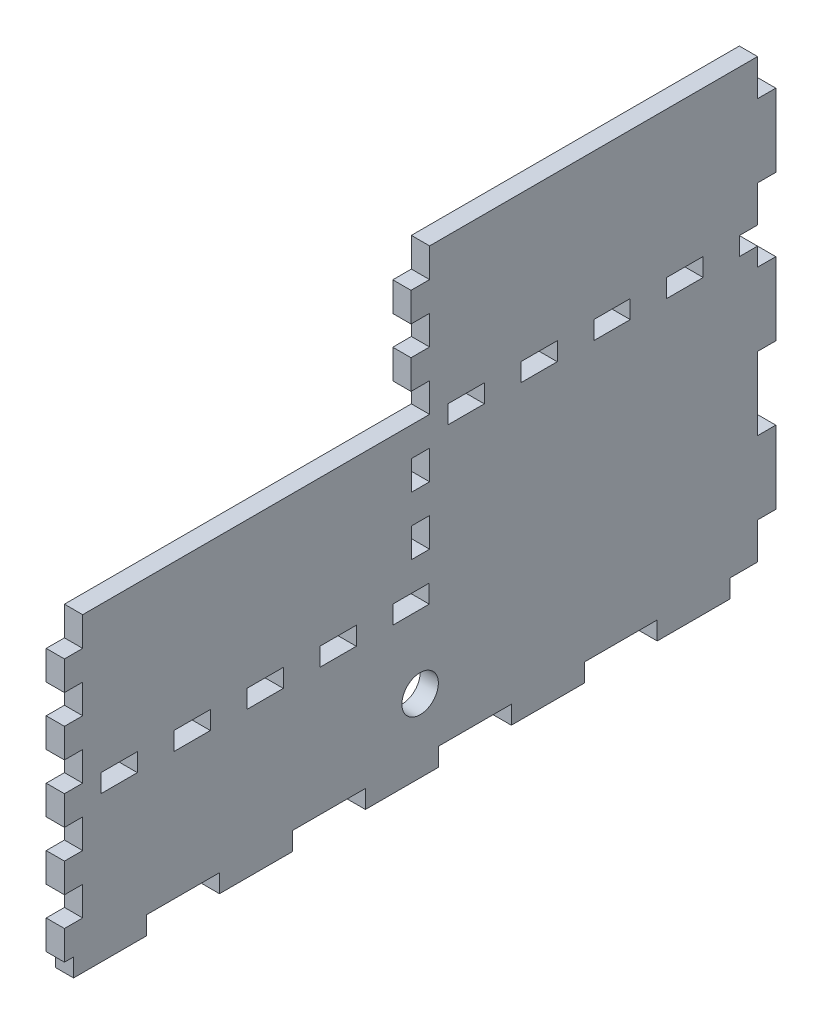
SolidWorks part; units mm, degrees
material "Pin"
ref_plane "Front" through (0, 0, 0) normal (0, 0, 1) x (1, 0, 0)
ref_plane "Top" through (0, 0, 0) normal (0, 1, 0) x (1, 0, 0)
ref_plane "Right" through (0, 0, 0) normal (1, 0, 0) x (0, 0, -1)
sketch "Esquisse1" plane through (0, 0, 0) normal (1, 0, 0) x (0, 0, -1)
  line L0 (-57.15, 38.1) -> (-57.15, 88.9)
  line L1 (-177.8, 38.1) -> (-57.15, 38.1)
  line L2 (-177.8, 38.1) -> (-177.8, -12.7)
  line L3 (-177.8, -12.7) -> (190.5, -12.7)
  line L7 (-57.15, 88.9) -> (63.5, 88.9)
  line L8 (63.5, 139.7) -> (190.5, 139.7)
  line L9 (63.5, 88.9) -> (63.5, 139.7)
  line L11 (190.5, -12.7) -> (190.5, 139.7)
  point P0 (0, 0)
  dimension "D1" = 368.3
  dimension "D2" = 50.8
  dimension "D3" = 50.8
  dimension "D4" = 50.8
  dimension "D5" = 120.65
  dimension "D6" = 127
  dimension "D7" = 12.7
  dimension "D8" = 190.5
extrude "Boss.-Extru.1" add sketch "Esquisse1" along normal blind 6.35
sketch "Esquisse4" plane through (6.35, 0, 0) normal (1, 0, 0) x (0, 0, -1)
  line L1 (-177.8, -12.7) -> (-171.45, -12.7)
  line L2 (-177.8, -12.7) -> (-177.8, -2.54)
  line L3 (-177.8, -2.54) -> (-171.45, -2.54)
  line L4 (-171.45, -12.7) -> (-171.45, -2.54)
  line L5 (-57.15, 38.1) -> (-50.8, 38.1)
  line L6 (-57.15, 38.1) -> (-57.15, 48.26)
  line L7 (-57.15, 48.26) -> (-50.8, 48.26)
  line L8 (-50.8, 38.1) -> (-50.8, 48.26)
  line L9 (63.5, 88.9) -> (69.9721, 88.9)
  line L10 (63.5, 88.9) -> (63.5, 99.06)
  line L11 (63.5, 99.06) -> (69.9721, 99.06)
  line L12 (69.9721, 88.9) -> (69.9721, 99.06)
  dimension "D1" = 10.16
  dimension "D2" = 6.35
  dimension "D3" = 10.16
  dimension "D4" = 10.16
  dimension "D5" = 6.35
  dimension "D6" = 6.4721
extrude "Enlèv. mat.-Extru.1" cut sketch "Esquisse4" against normal through all
pattern_linear "Répétition linéaire3" count 3 spacing 20.32 along (0, 1, 0) of "Enlèv. mat.-Extru.1"
sketch "Esquisse6" plane through (6.35, 0, 0) normal (1, 0, 0) x (0, 0, -1)
  line L0 (-171.45, -12.7) -> (190.5, -12.7) construction
  line L1 (-155.575, -12.7) -> (-130.175, -12.7)
  line L2 (-155.575, -12.7) -> (-155.575, -19.05)
  line L3 (-155.575, -19.05) -> (-130.175, -19.05)
  line L4 (-130.175, -12.7) -> (-130.175, -19.05)
  line L5 (-171.45, -12.7) -> (-171.45, -2.54) construction
  dimension "D1" = 6.35
  dimension "D2" = 25.4
  dimension "D3" = 15.875
extrude "Boss.-Extru.3" add sketch "Esquisse6" against normal blind 6.35
pattern_linear "Répétition linéaire4" count 7 spacing 50.8 along (0, 0, -1) of "Boss.-Extru.3"
sketch "Esquisse7" plane through (6.35, 0, 0) normal (1, 0, 0) x (0, 0, -1)
  line L0 (-50.8, 38.1) -> (-50.8, 48.26) construction
  line L1 (-57.15, 27.94) -> (-50.8, 27.94)
  line L2 (-57.15, 27.94) -> (-57.15, 17.78)
  line L3 (-57.15, 17.78) -> (-50.8, 17.78)
  line L4 (-50.8, 27.94) -> (-50.8, 17.78)
  line L5 (69.9721, 88.9) -> (69.9721, 99.06) construction
  line L6 (63.6221, 78.74) -> (69.9721, 78.74)
  line L7 (63.6221, 78.74) -> (63.6221, 68.58)
  line L8 (63.6221, 68.58) -> (69.9721, 68.58)
  line L9 (69.9721, 78.74) -> (69.9721, 68.58)
  line L10 (69.9721, 88.9) -> (-50.8, 88.9) construction
  line L11 (-50.8, 38.1) -> (-171.45, 38.1) construction
  line L12 (-57.15, 7.62) -> (-50.8, 7.62)
  line L13 (-57.15, 7.62) -> (-57.15, -2.54)
  line L14 (-57.15, -2.54) -> (-50.8, -2.54)
  line L15 (-50.8, 7.62) -> (-50.8, -2.54)
  line L16 (63.6221, 58.42) -> (69.9721, 58.42)
  line L17 (63.6221, 58.42) -> (63.6221, 48.26)
  line L18 (63.6221, 48.26) -> (69.9721, 48.26)
  line L19 (69.9721, 58.42) -> (69.9721, 48.26)
  line L44 (-57.15, -12.7) -> (-50.8, -12.7) [skipped]
  line L45 (-57.15, -12.7) -> (-57.15, -22.86) [skipped]
  line L46 (-57.15, -22.86) -> (-50.8, -22.86) [skipped]
  line L47 (-50.8, -12.7) -> (-50.8, -22.86) [skipped]
  line L48 (-57.15, -33.02) -> (-50.8, -33.02) [skipped]
  line L49 (-57.15, -33.02) -> (-57.15, -43.18) [skipped]
  line L50 (-57.15, -43.18) -> (-50.8, -43.18) [skipped]
  line L51 (-50.8, -33.02) -> (-50.8, -43.18) [skipped]
  line L52 (-57.15, -53.34) -> (-50.8, -53.34) [skipped]
  line L53 (-57.15, -53.34) -> (-57.15, -63.5) [skipped]
  line L54 (-57.15, -63.5) -> (-50.8, -63.5) [skipped]
  line L55 (-50.8, -53.34) -> (-50.8, -63.5) [skipped]
  line L56 (63.6221, 38.1) -> (69.9721, 38.1) [skipped]
  line L57 (63.6221, 38.1) -> (63.6221, 27.94) [skipped]
  line L58 (63.6221, 27.94) -> (69.9721, 27.94) [skipped]
  line L59 (69.9721, 38.1) -> (69.9721, 27.94) [skipped]
  line L60 (63.6221, 17.78) -> (69.9721, 17.78) [skipped]
  line L61 (63.6221, 17.78) -> (63.6221, 7.62) [skipped]
  line L62 (63.6221, 7.62) -> (69.9721, 7.62) [skipped]
  line L63 (69.9721, 17.78) -> (69.9721, 7.62) [skipped]
  line L64 (63.6221, -2.54) -> (69.9721, -2.54) [skipped]
  line L65 (63.6221, -2.54) -> (63.6221, -12.7) [skipped]
  line L66 (63.6221, -12.7) -> (69.9721, -12.7) [skipped]
  line L67 (69.9721, -2.54) -> (69.9721, -12.7) [skipped]
  dimension "D1" = 6.35
  dimension "D2" = 10.16
  dimension "D3" = 6.35
  dimension "D4" = 10.16
  dimension "D5" = 10.16
  dimension "D6" = 10.16
  dimension "D7" = 5
extrude "Enlèv. mat.-Extru.2" cut sketch "Esquisse7" against normal blind 6.35
sketch "Esquisse8" plane through (6.35, 0, 0) normal (1, 0, 0) x (0, 0, -1)
  line L0 (-50.8, 38.1) -> (-171.45, 38.1) construction
  line L1 (-44.45, 38.1) -> (-31.75, 38.1)
  line L2 (-44.45, 38.1) -> (-44.45, 31.75)
  line L3 (-44.45, 31.75) -> (-31.75, 31.75)
  line L4 (-31.75, 38.1) -> (-31.75, 31.75)
  line L5 (-50.8, 38.1) -> (-50.8, 48.26) construction
  line L6 (69.9721, 88.9) -> (69.9721, 99.06) construction
  line L7 (76.3221, 88.9) -> (89.0221, 88.9)
  line L8 (76.3221, 88.9) -> (76.3221, 82.55)
  line L9 (76.3221, 82.55) -> (89.0221, 82.55)
  line L10 (89.0221, 88.9) -> (89.0221, 82.55)
  line L11 (69.9721, 88.9) -> (-50.8, 88.9) construction
  dimension "D1" = 6.35
  dimension "D2" = 12.7
  dimension "D3" = 6.35
  dimension "D4" = 6.35
  dimension "D5" = 12.7
  dimension "D6" = 6.35
extrude "Enlèv. mat.-Extru.3" cut sketch "Esquisse8" against normal blind 6.35
pattern_linear "Répétition linéaire6" count 5 spacing 25.4 along (0, 0, -1) of "Enlèv. mat.-Extru.3"
sketch "Esquisse9" plane through (6.35, 0, 0) normal (1, 0, 0) x (0, 0, -1)
  line L0 (190.5, 88.9) -> (190.5, 139.7) construction
  line L1 (190.5, 101.6) -> (184.15, 101.6)
  line L2 (190.5, 101.6) -> (190.5, 76.2)
  line L3 (190.5, 76.2) -> (184.15, 76.2)
  line L4 (184.15, 101.6) -> (184.15, 76.2)
  line L5 (190.5, 139.7) -> (69.9721, 139.7) construction
  dimension "D1" = 6.35
  dimension "D2" = 25.4
  dimension "D3" = 38.1
extrude "Enlèv. mat.-Extru.4" cut sketch "Esquisse9" against normal blind 6.35
pattern_linear "Répétition linéaire7" count 3 spacing 50.8 along (0, -1, 0) of "Enlèv. mat.-Extru.4"
sketch "Esquisse10" plane through (6.35, 0, 0) normal (1, 0, 0) x (0, 0, -1)
  line L1 (190.5, 139.7) -> (184.15, 139.7)
  line L2 (190.5, 139.7) -> (190.5, 127)
  line L3 (190.5, 127) -> (184.15, 127)
  line L4 (184.15, 139.7) -> (184.15, 127)
  dimension "D1" = 6.35
  dimension "D2" = 12.7
extrude "Enlèv. mat.-Extru.5" cut sketch "Esquisse10" against normal blind 6.35
sketch "Sketch1" plane through (6.35, 0, 0) normal (1, 0, 0) x (0, 0, -1)
  line L0 (-57.15, 27.94) -> (-57.15, 17.78) construction
  line L1 (-177.8, 38.1) -> (-57.15, 38.1)
  line L2 (-177.8, 38.1) -> (-177.8, -19.05)
  line L3 (-177.8, -19.05) -> (-57.15, -19.05)
  line L4 (-57.15, 38.1) -> (-57.15, -19.05)
  line L5 (-104.775, -19.05) -> (-79.375, -19.05) construction
  line L6 (-177.8, 27.94) -> (-177.8, 17.78) construction
  line L7 (-50.8, 38.1) -> (-171.45, 38.1) construction
extrude "Cut-Extrude1" cut sketch "Sketch1" against normal through all
sketch "Esquisse11" plane through (0, 0, 0) normal (-1, 0, 0) x (0, 0, 1)
  line L0 (-190.5, 0) -> (-190.5, 25.4) construction
  line L1 (-47.625, -19.05) -> (-73.025, -19.05) construction
  circle A0 centre (-66.675, 6.35) radius 6.35
  point P4 (0, 0)
  dimension "D3" = 12.7
  dimension "D1" = 123.825
  dimension "D2" = 25.4
extrude "Enlèv. mat.-Extru.6" cut sketch "Esquisse11" against normal up to next
